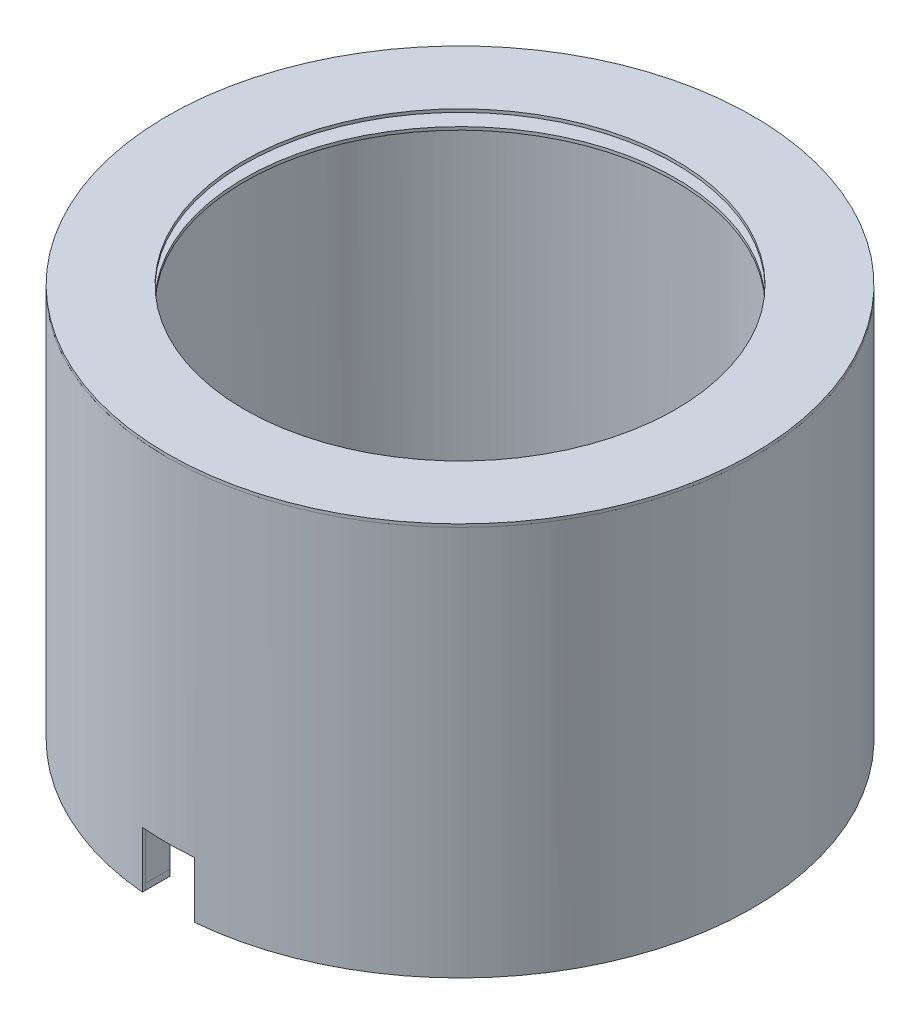
SolidWorks part; units mm, degrees
ref_plane "Front Plane" through (0, 0, 0) normal (0, 0, 1) x (1, 0, 0)
ref_plane "Top Plane" through (0, 0, 0) normal (0, 1, 0) x (1, 0, 0)
ref_plane "Right Plane" through (0, 0, 0) normal (1, 0, 0) x (0, 0, -1)
sketch "Sketch1" plane through (0, 0, 0) normal (0, 1, 0) x (1, 0, 0)
  circle A0 centre (0, 0) radius 235
  circle A1 centre (0, 0) radius 237.5
  dimension "D1" = 470
  dimension "D2" = 2.5
extrude "Boss-Extrude1" add sketch "Sketch1" along normal blind 316.6
ref_plane "Plane1" through (0, 0, 237.5) normal (0, 0, 1) x (1, 0, 0)
sketch "Sketch3" plane through (0, 0, 0) normal (0, 1, 0) x (1, 0, 0)
  circle A2 centre (0, 0) radius 215
  circle A3 centre (0, 0) radius 215
  circle A5 centre (0, 0) radius 235
  circle A6 centre (0, 0) radius 235
  dimension "D1" = 20
  dimension "D2" = 0
extrude "Boss-Extrude2" add sketch "Sketch3" along normal blind 5 separate body
sketch "Sketch7" plane through (0, 316.6, 0) normal (0, 1, 0) x (1, 0, 0)
  circle A1 centre (0, 0) radius 175
  circle A2 centre (0, 0) radius 237.5
  circle A3 centre (0, 0) radius 237.5
  dimension "D1" = 0
extrude "Boss-Extrude3" add sketch "Sketch7" along normal blind 2.5 separate body
ref_plane "Plane2" through (0, 306.6, 0) normal (0, 1, 0) x (1, 0, 0)
sketch "Sketch8" plane through (0, 306.6, 0) normal (0, 1, 0) x (1, 0, 0)
  circle A11 centre (0, 0) radius 175
  circle A13 centre (0, 0) radius 175
  circle A15 centre (0, 0) radius 235
  circle A16 centre (0, 0) radius 235
  dimension "D1" = 0
  dimension "D2" = 0
extrude "Boss-Extrude4" add sketch "Sketch8" against normal blind 2.5 separate body
sketch "Sketch9" plane through (0, 5, 0) normal (0, 1, 0) x (1, 0, 0)
  circle A2 centre (0, 0) radius 235
  circle A3 centre (0, 0) radius 235
  dimension "D1" = 0
extrude "Boss-Extrude5" add sketch "Sketch9" along normal up to surface (299.1 mm away) separate body contours A3 up to face at (0, 304.1, 175)
sketch "Sketch14" plane through (0, 304.1, 0) normal (0, -1, 0) x (1, 0, 0)
  circle A0 centre (0, 0) radius 220
sketch "Sketch5" plane through (0, 0, 237.5) normal (0, 0, 1) x (1, 0, 0)
  line L1 (-21.25, 45.6) -> (21.25, 45.6)
  line L2 (-21.25, 45.6) -> (-21.25, 0)
  line L3 (-21.25, 0) -> (21.25, 0)
  line L4 (21.25, 45.6) -> (21.25, 0)
  point P4 (0, 0)
  dimension "D1" = 45.6
  dimension "D2" = 42.5
sketch "Sketch13" plane through (0, 0, 0) normal (0, 0, 1) x (1, 0, 0)
  line L6 (-215, 5) -> (215, 5) construction
  line L8 (0, 5) -> (0, 304.1) construction
  line L10 (0, 5) -> (-215, 5)
  line L11 (0, 5) -> (0, 304.1)
  line L14 (-220, 304.1) -> (0, 304.1)
  line L15 (-220, 304.1) -> (220, 304.1)
  line L16 (-220, 304.1) -> (220, 304.1) construction
  line L17 (-220, 304.1) -> (-215, 5)
  dimension "D1" = 0
revolve "Cut-Revolve2" cut sketch "Sketch13" angle 360 about L11
extrude "Cut-Extrude5" cut sketch "Sketch5" against normal up to surface (22.8707 mm away)
